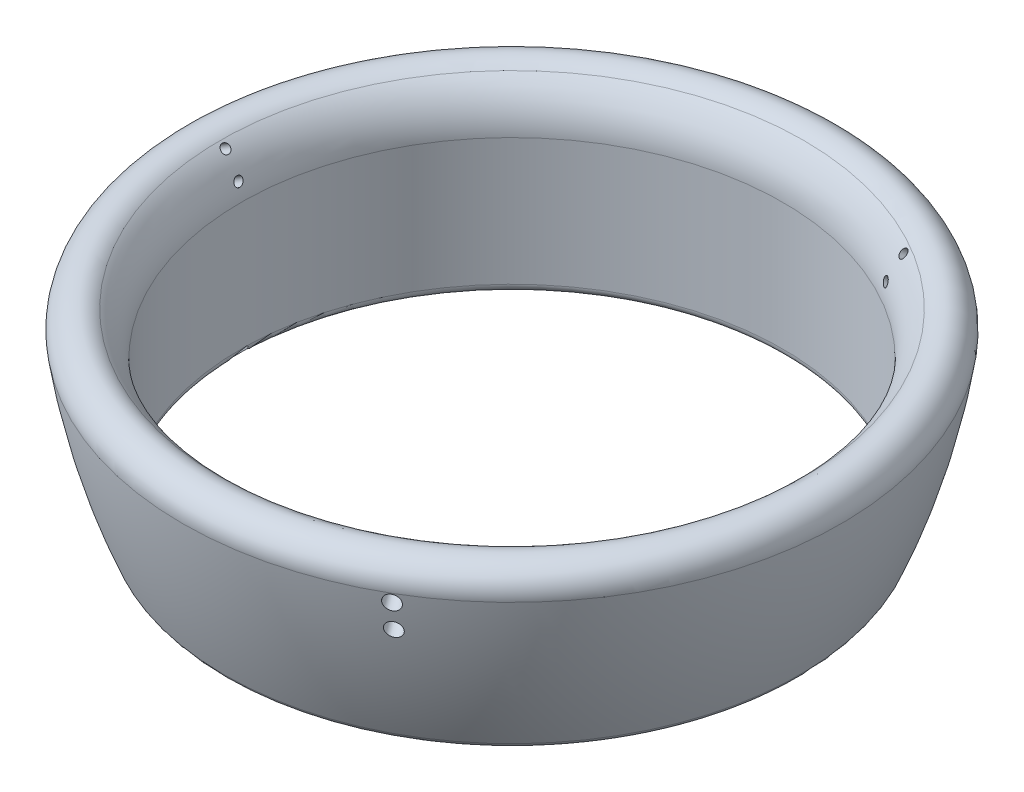
SolidWorks part; units mm, degrees
ref_plane "Front Plane" through (0, 0, 0) normal (0, 0, 1) x (1, 0, 0)
ref_plane "Top Plane" through (0, 0, 0) normal (0, 1, 0) x (1, 0, 0)
ref_plane "Right Plane" through (0, 0, 0) normal (1, 0, 0) x (0, 0, -1)
ref_plane "Plane1" through (0, 0, 0) normal (0, 0, -1) x (-1, 0, 0)
sketch "Sketch1" plane through (0, 0, 0) normal (0, 0, -1) x (-1, 0, 0)
  line L0 (-320, -150) -> (-320, 0)
  line L1 (-330, -140) -> (-330, -150)
  line L2 (-330, -150) -> (-331.7365, -140.1519)
  line L3 (0, -160) -> (0, 57.5) construction
  arc A0 (-320, 0) -> (-344.3509, 51.3051) centre (-386.2231, 0) ccw
  arc A1 (-344.3509, 51.3051) -> (-388.9174, 25.8073) centre (-361.7389, 30) ccw
  arc A2 (-388.9174, 25.8073) -> (-339.2624, -153.7693) centre (401.7301, 147.7768) ccw
  arc A3 (-339.2624, -153.7693) -> (-320, -150) centre (-330, -150) ccw
  arc A4 (-331.7365, -140.1519) -> (-330, -140) centre (-330, -150) cw
revolve "Revolve1" add sketch "Sketch1" angle 360 about L3
ref_plane "Plane2" through (-284.3439, -177.6778, 0) normal (-0.848, -0.5299, 0) x (0, 0, 1)
hole_wizard "Hole1" positions "Sketch3" profile "Sketch2" legacy
sketch "Sketch3" plane through (-284.3439, -177.6778, 0) normal (-0.848, -0.5299, 0) x (0, 0, 1)
  point P0 (0, 187.9874)
sketch "Sketch2" plane through (-383.962, -18.2555, 0) normal (0, 0, 1) x (0.5299, -0.848, 0)
  line L0 (0, 0) -> (0, 695.8558)
  line L1 (0, 695.8558) -> (5.25, 695.8558)
  line L2 (5.25, 695.8558) -> (5.25, 14.0411)
  line L3 (5.25, 14.0411) -> (9, 14.0411)
  line L4 (9, 14.0411) -> (9, 0)
  line L5 (9, 0) -> (0, 0)
  line L6 (0, 110) -> (0, -10) construction
  dimension "Diameter" = 10.5
  dimension "Depth" = 695.8558
  dimension "C-Bore Diameter" = 18
  dimension "C-Bore Depth" = 14.0411
ref_plane "Plane3" through (-274.7759, -171.6991, 0) normal (-0.848, -0.5299, 0) x (0, 0, 1)
hole_wizard "Hole2" positions "Sketch5" profile "Sketch4" legacy
sketch "Sketch5" plane through (-274.7759, -171.6991, 0) normal (-0.848, -0.5299, 0) x (0, 0, 1)
  point P0 (0, 217.9874)
sketch "Sketch4" plane through (-390.2917, 13.1647, 0) normal (0, 0, 1) x (0.5299, -0.848, 0)
  line L0 (0, 0) -> (0, 684.5735)
  line L1 (0, 684.5735) -> (5.25, 684.5735)
  line L2 (5.25, 684.5735) -> (5.25, 14.4556)
  line L3 (5.25, 14.4556) -> (9, 14.4556)
  line L4 (9, 14.4556) -> (9, 0)
  line L5 (9, 0) -> (0, 0)
  line L6 (0, 110) -> (0, -10) construction
  dimension "Diameter" = 10.5
  dimension "Depth" = 684.5735
  dimension "C-Bore Diameter" = 18
  dimension "C-Bore Depth" = 14.4556
ref_plane "Plane4" through (137.388, -171.6991, 237.9629) normal (0.424, -0.5299, 0.7344) x (0.9057, 0.2481, -0.3439)
hole_wizard "Hole3" positions "Sketch7" profile "Sketch6" legacy
sketch "Sketch7" plane through (137.388, -171.6991, 237.9629) normal (0.424, -0.5299, 0.7344) x (0.9057, 0.2481, -0.3439)
  point P0 (63.775, 208.4496)
sketch "Sketch6" plane through (195.1458, 13.1647, 338.0025) normal (0.7035, 0.7035, 0.1014) x (0.5704, -0.4736, -0.6711)
  line L0 (0, 0) -> (0, 805.451)
  line L1 (0, 805.451) -> (5.25, 805.451)
  line L2 (5.25, 805.451) -> (5.25, 14.4556)
  line L3 (5.25, 14.4556) -> (9, 14.4556)
  line L4 (9, 14.4556) -> (9, 0)
  line L5 (9, 0) -> (0, 0)
  line L6 (0, 110) -> (0, -10) construction
  dimension "Diameter" = 10.5
  dimension "Depth" = 805.451
  dimension "C-Bore Diameter" = 18
  dimension "C-Bore Depth" = 14.4556
ref_plane "Plane5" through (142.172, -177.6778, 246.2491) normal (0.424, -0.5299, 0.7344) x (0.9057, 0.2481, -0.3439)
hole_wizard "Hole4" positions "Sketch9" profile "Sketch8" legacy
sketch "Sketch9" plane through (142.172, -177.6778, 246.2491) normal (0.424, -0.5299, 0.7344) x (0.9057, 0.2481, -0.3439)
  point P0 (54.9981, 179.7622)
sketch "Sketch8" plane through (191.981, -18.2555, 332.5209) normal (0.7035, 0.7035, 0.1014) x (0.5704, -0.4736, -0.6711)
  line L0 (0, 0) -> (0, 816.7333)
  line L1 (0, 816.7333) -> (5.25, 816.7333)
  line L2 (5.25, 816.7333) -> (5.25, 14.0411)
  line L3 (5.25, 14.0411) -> (9, 14.0411)
  line L4 (9, 14.0411) -> (9, 0)
  line L5 (9, 0) -> (0, 0)
  line L6 (0, 110) -> (0, -10) construction
  dimension "Diameter" = 10.5
  dimension "Depth" = 816.7333
  dimension "C-Bore Diameter" = 18
  dimension "C-Bore Depth" = 14.0411
ref_plane "Plane6" through (137.388, -171.6991, -237.9629) normal (0.424, -0.5299, -0.7344) x (-0.9057, -0.2481, -0.3439)
hole_wizard "Hole5" positions "Sketch11" profile "Sketch10" legacy
sketch "Sketch11" plane through (137.388, -171.6991, -237.9629) normal (0.424, -0.5299, -0.7344) x (-0.9057, -0.2481, -0.3439)
  point P0 (-63.775, 208.4496)
sketch "Sketch10" plane through (195.1458, 13.1647, -338.0025) normal (0.7035, 0.7035, -0.1014) x (-0.5704, 0.4736, -0.6711)
  line L0 (0, 0) -> (0, 805.451)
  line L1 (0, 805.451) -> (5.25, 805.451)
  line L2 (5.25, 805.451) -> (5.25, 14.4556)
  line L3 (5.25, 14.4556) -> (9, 14.4556)
  line L4 (9, 14.4556) -> (9, 0)
  line L5 (9, 0) -> (0, 0)
  line L6 (0, 110) -> (0, -10) construction
  dimension "Diameter" = 10.5
  dimension "Depth" = 805.451
  dimension "C-Bore Diameter" = 18
  dimension "C-Bore Depth" = 14.4556
ref_plane "Plane7" through (142.172, -177.6778, -246.2491) normal (0.424, -0.5299, -0.7344) x (-0.9057, -0.2481, -0.3439)
hole_wizard "Hole6" positions "Sketch13" profile "Sketch12" legacy
sketch "Sketch13" plane through (142.172, -177.6778, -246.2491) normal (0.424, -0.5299, -0.7344) x (-0.9057, -0.2481, -0.3439)
  point P0 (-54.9981, 179.7622)
sketch "Sketch12" plane through (191.981, -18.2555, -332.5209) normal (0.7035, 0.7035, -0.1014) x (-0.5704, 0.4736, -0.6711)
  line L0 (0, 0) -> (0, 816.7333)
  line L1 (0, 816.7333) -> (5.25, 816.7333)
  line L2 (5.25, 816.7333) -> (5.25, 14.0411)
  line L3 (5.25, 14.0411) -> (9, 14.0411)
  line L4 (9, 14.0411) -> (9, 0)
  line L5 (9, 0) -> (0, 0)
  line L6 (0, 110) -> (0, -10) construction
  dimension "Diameter" = 10.5
  dimension "Depth" = 816.7333
  dimension "C-Bore Diameter" = 18
  dimension "C-Bore Depth" = 14.0411
